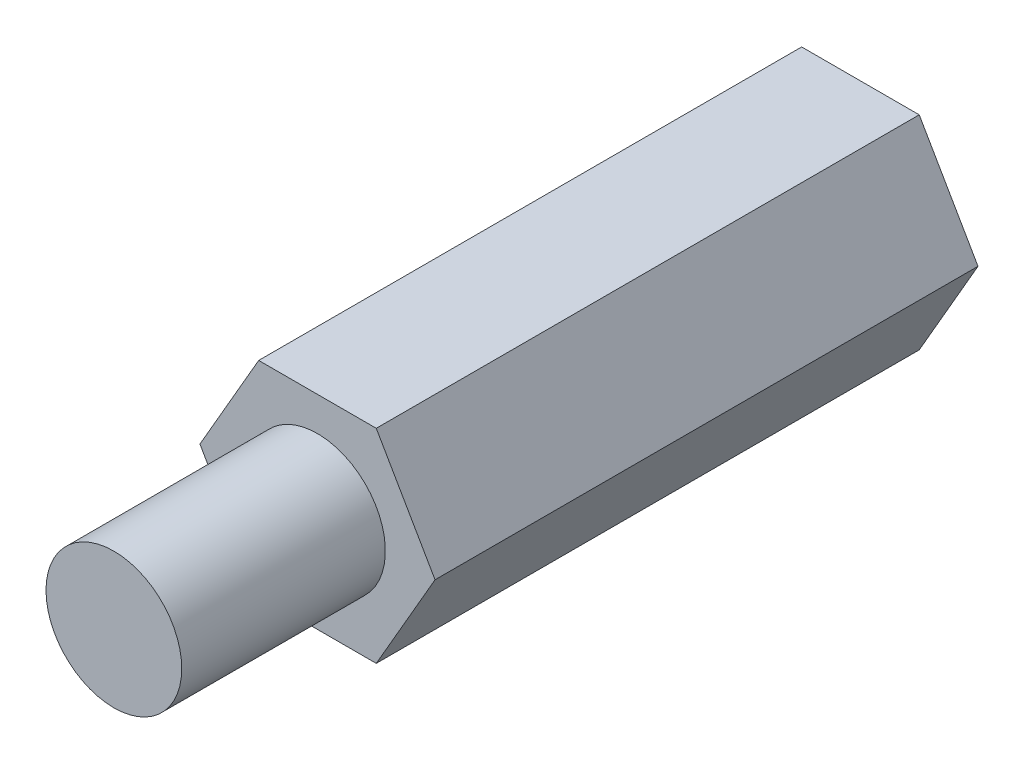
SolidWorks part; units mm, degrees
ref_plane "前视基准面" through (0, 0, 0) normal (0, 0, 1) x (1, 0, 0)
ref_plane "上视基准面" through (0, 0, 0) normal (0, 1, 0) x (1, 0, 0)
ref_plane "右视基准面" through (0, 0, 0) normal (1, 0, 0) x (0, 0, -1)
sketch "草图1" plane through (0, 0, 0) normal (0, 0, 1) x (1, 0, 0)
  line L0 (-28.6627, 0) -> (33.6774, 0) construction
  line L1 (1.7321, -3) -> (3.4641, 0)
  line L2 (3.4641, 0) -> (1.7321, 3)
  line L3 (1.7321, 3) -> (-1.7321, 3)
  line L4 (-1.7321, 3) -> (-3.4641, 0)
  line L5 (-3.4641, 0) -> (-1.7321, -3)
  line L6 (-1.7321, -3) -> (1.7321, -3)
  circle A0 centre (0, 0) radius 3 construction
  dimension "D1" = 6
extrude "拉伸1" add sketch "草图1" along normal blind 16
sketch "草图2" plane through (0, 0, 16) normal (0, 0, 1) x (1, 0, 0)
  circle A0 centre (0, 0) radius 2
  dimension "D1" = 4
extrude "拉伸2" add sketch "草图2" along normal blind 6
hole_wizard "M4 螺纹孔1" positions "3D草图2" profile "草图5" tap size "M4" standard "ISO"
sketch3d "3D草图2"
  point P0 (0, 0, 0)
  point P2 (0, 0, 0)
  point P3 (0, 0, 0)
  point P4 (0, 0, 0)
cosmetic thread "孔螺蚊线1"
sketch "草图5" plane through (0, 0, 0) normal (1, 0, 0) x (0, 1, 0)
  line L0 (0, 0) -> (0, 12.4914)
  line L1 (0, 12.4914) -> (1.65, 11.5)
  line L2 (1.65, 11.5) -> (1.65, 0)
  line L5 (1.65, 0) -> (0, 0)
  line L10 (0, 12.4914) -> (-1.65, 11.5) construction
  line L11 (0, -6.35) -> (0, 107.95) construction
  dimension "蹟恇謂郰芛眻噤" = 3.3
  dimension "蹟恇謂郰芛旮僅" = 11.5
  dimension "絳芛褒僅" = 118
sketch "草图6" plane through (0, 0, 0) normal (0, 0, -1) x (-1, 0, 0)
  circle A0 centre (0, 0) radius 1.5
  dimension "D1" = 3
extrude "拉伸3" [suppressed] add sketch "草图6" along normal blind 10
